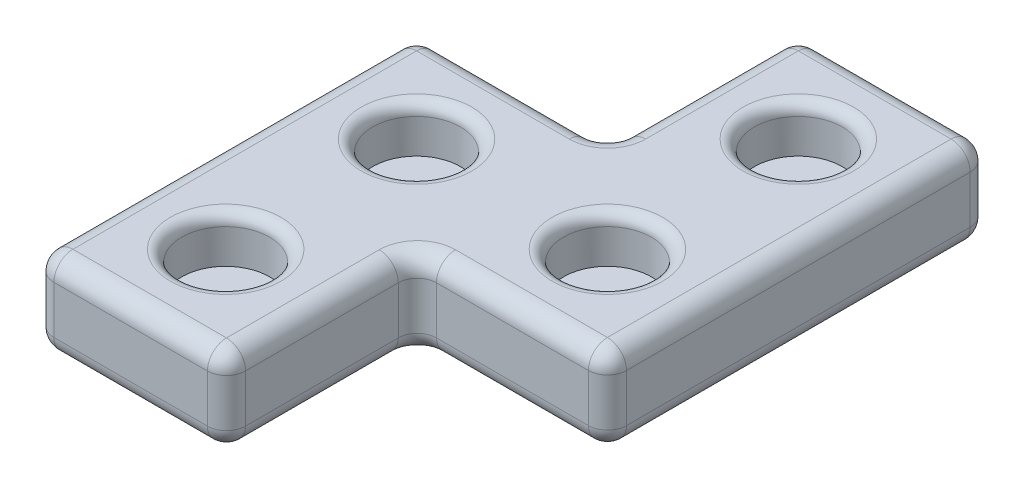
SolidWorks part; units mm, degrees
ref_plane "Front Plane" through (0, 0, 0) normal (0, 0, 1) x (1, 0, 0)
ref_plane "Top Plane" through (0, 0, 0) normal (0, 1, 0) x (1, 0, 0)
ref_plane "Right Plane" through (0, 0, 0) normal (1, 0, 0) x (0, 0, -1)
sketch "Sketch1" plane through (0, 0, 0) normal (0, 1, 0) x (1, 0, 0)
  line L0 (-7.6659, 2.6651) -> (-7.6659, 12.8251)
  line L1 (-6.3959, 14.0951) -> (3.7641, 14.0951)
  line L2 (5.0341, 12.8251) -> (5.0341, -10.0349)
  line L3 (3.7641, -11.3049) -> (-6.3409, -11.3049)
  line L4 (-7.6109, -12.5749) -> (-7.6109, -22.7349)
  line L5 (-8.8809, -24.0049) -> (-19.0959, -24.0049)
  line L6 (-20.3659, -22.7349) -> (-20.3659, 0.1251)
  line L7 (-19.0959, 1.3951) -> (-8.9359, 1.3951)
  arc A0 (-7.6659, 2.6651) -> (-8.9359, 1.3951) centre (-8.9359, 2.6651) cw
  arc A1 (-6.3409, -11.3049) -> (-7.6109, -12.5749) centre (-6.3409, -12.5749) ccw
  arc A2 (-7.6109, -22.7349) -> (-8.8809, -24.0049) centre (-8.8809, -22.7349) cw
  arc A3 (-19.0959, -24.0049) -> (-20.3659, -22.7349) centre (-19.0959, -22.7349) cw
  arc A4 (-20.3659, 0.1251) -> (-19.0959, 1.3951) centre (-19.0959, 0.1251) cw
  arc A5 (5.0341, -10.0349) -> (3.7641, -11.3049) centre (3.7641, -10.0349) cw
  arc A6 (-7.6659, 12.8251) -> (-6.3959, 14.0951) centre (-6.3959, 12.8251) cw
  arc A7 (3.7641, 14.0951) -> (5.0341, 12.8251) centre (3.7641, 12.8251) cw
  point P10 (-7.6659, 1.3951)
  point P13 (-7.6109, -11.3049)
  point P18 (-20.3659, -24.0049)
  point P21 (-20.3659, 1.3951)
  point P24 (5.0341, -11.3049)
  point P27 (-7.6659, 14.0951)
  point P30 (5.0341, 14.0951)
  dimension "D7" = 1.27
  dimension "D1" = 12.7
  dimension "D2" = 25.4
  dimension "D3" = 12.7
  dimension "D4" = 25.4
  dimension "D5" = 12.645
  dimension "D6" = 12.7
extrude "Boss-Extrude1" add sketch "Sketch1" along normal blind 5.715
sketch "Sketch2" plane through (0, 5.715, 0) normal (0, 1, 0) x (1, 0, 0)
  line L0 (5.0341, -10.0349) -> (5.0341, 12.8251) construction
  line L1 (-19.0959, -24.0049) -> (-8.8809, -24.0049) construction
  circle A0 centre (-1.3159, 7.7451) radius 2.921
  circle A1 centre (-14.0159, -4.9549) radius 2.921
  circle A2 centre (-14.0159, -17.6549) radius 2.921
  circle A3 centre (-1.3159, -4.9549) radius 2.921
  dimension "D1" = 6.35
  dimension "D2" = 12.7
  dimension "D3" = 12.7
  dimension "D4" = 12.7
  dimension "D5" = 6.35
extrude "Cut-Extrude1" cut sketch "Sketch2" against normal blind 3.048
fillet "Fillet1" radius 1.27 16 edges at (-1.2884, 5.715, 11.3049) (-7.6109, 5.715, 17.6549) (-13.9884, 5.715, 24.0049) (-20.3659, 5.715, 11.3049) (-14.0159, 5.715, -1.3951) (-7.6659, 5.715, -7.7451) (-1.3159, 5.715, -14.0951) (5.0341, 5.715, -1.3951) (4.6621, 5.715, 10.9329) (-7.2389, 5.715, 11.6769) (-7.9829, 5.715, 23.6329) (-19.9939, 5.715, 23.6329) (-19.9939, 5.715, -1.0231) (-8.0379, 5.715, -1.7671) (-7.2939, 5.715, -13.7231) (4.6621, 5.715, -13.7231)
fillet "Fillet2" radius 1.27 16 edges at (-1.3159, 0, -14.0951) (-7.6659, 0, -7.7451) (-14.0159, 0, -1.3951) (-20.3659, 0, 11.3049) (-13.9884, 0, 24.0049) (-7.6109, 0, 17.6549) (-1.2884, 0, 11.3049) (5.0341, 0, -1.3951) (4.6621, 0, 10.9329) (-7.2389, 0, 11.6769) (-7.9829, 0, 23.6329) (-19.9939, 0, 23.6329) (-19.9939, 0, -1.0231) (-8.0379, 0, -1.7671) (-7.2939, 0, -13.7231) (4.6621, 0, -13.7231)
fillet "Fillet3" radius 0.762 4 edges at (-14.0159, 5.715, 20.5759) (-14.0159, 5.715, 7.8759) (-1.3159, 5.715, 7.8759) (-1.3159, 5.715, -4.8241)
